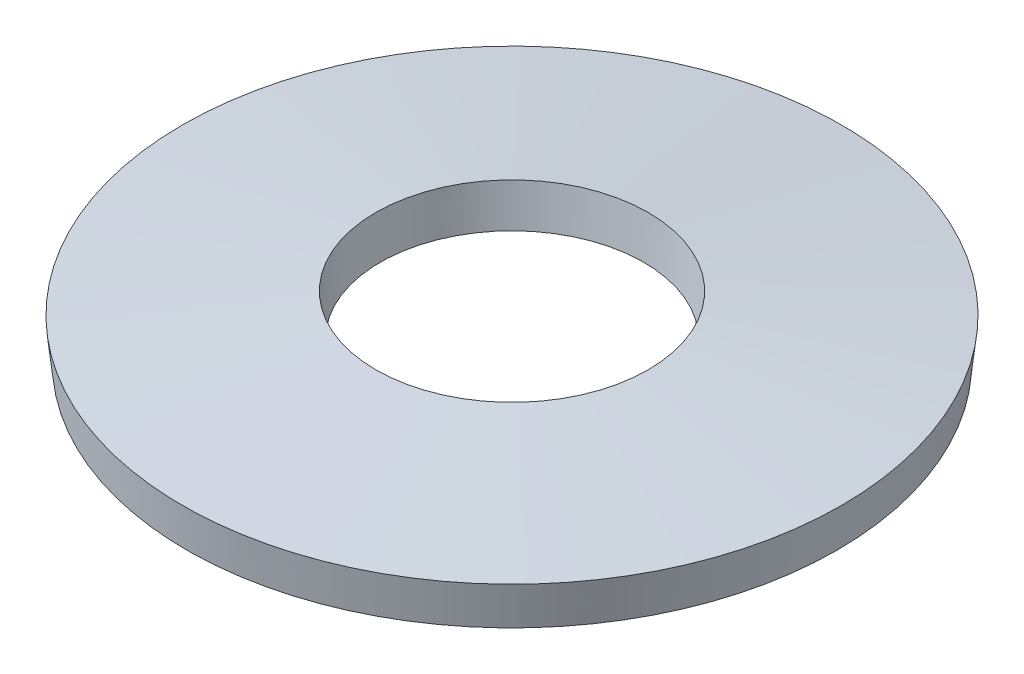
SolidWorks part; units mm, degrees
material "Cast Alloy Steel"
ref_plane "Front Plane" through (0, 0, 0) normal (0, 0, 1) x (1, 0, 0)
ref_plane "Top Plane" through (0, 0, 0) normal (0, 1, 0) x (1, 0, 0)
ref_plane "Right Plane" through (0, 0, 0) normal (1, 0, 0) x (0, 0, -1)
sketch "Sketch1" plane through (0, 0, 0) normal (0, 0, 1) x (1, 0, 0)
  line L0 (0, -0.9273) -> (0, 0.9273) construction
  line L1 (3.9464, 0) -> (4, 0.4971)
  line L2 (4, 0.4971) -> (1.6536, 0.75)
  line L3 (1.6536, 0.75) -> (1.6, 0.2529)
  line L4 (1.6, 0.2529) -> (3.9464, 0)
  dimension "D1" = 3.2
  dimension "D2" = 8
  dimension "D3" = 0.5
  dimension "D4" = 0.75
revolve "Revolve1" add sketch "Sketch1" angle 360 about L0
